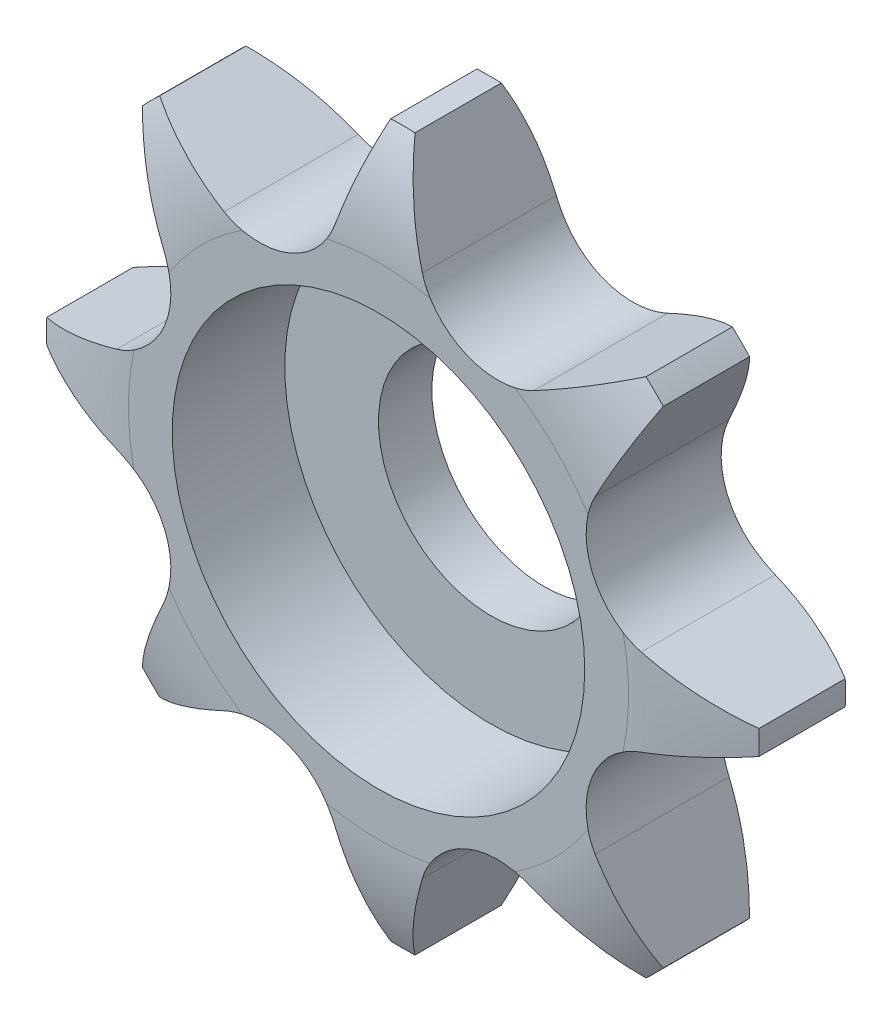
SolidWorks part; units mm, degrees
ref_plane "前视基准面" through (0, 0, 0) normal (0, 0, 1) x (1, 0, 0)
ref_plane "上视基准面" through (0, 0, 0) normal (0, 1, 0) x (1, 0, 0)
ref_plane "右视基准面" through (0, 0, 0) normal (1, 0, 0) x (0, 0, -1)
sketch "草图1" plane through (0, 0, 0) normal (1, 0, 0) x (0, 0, -1)
  line L0 (0, 0) -> (-25, 0) construction
  line L1 (0, 0) -> (0, 10)
  line L2 (0, 10) -> (-17.8, 10)
  line L3 (-25, 5) -> (0, 5)
  line L4 (-19.1, 19) -> (-25, 19)
  line L5 (-25, 19) -> (-25, 0)
  line L6 (-25, 16.59) -> (-17.8, 16.59) construction
  line L8 (-21.4, 16.59) -> (-21.4, 19) construction
  line L9 (-17.8, 16.59) -> (-17.8, 10)
  line L10 (-18, 10) -> (-18, 16.59)
  arc A0 (-17.8, 13.3334) -> (-19.1, 19) centre (-30.8, 13.3334) ccw
  arc A1 (-18, 13.3334) -> (-19.3, 19) centre (-31, 13.3334) ccw
  point P14 (-25, 4)
  point P15 (-18, 10)
  point P17 (-4, 10)
  point P18 (9.9, 10)
  dimension "D1" = 10
  dimension "r" = 13
  dimension "D3" = 13
  dimension "B1" = 7.2
  dimension "D2" = 1.3
  dimension "A" = 25
  dimension "de" = 38
  dimension "Dp" = 33.18
  dimension "Dm" = 20
  dimension "C" = 1.3
  dimension "Z" = 8
  dimension "(b1)" = 7
  dimension "B2" = 21
  dimension "B3" = 34.9
sketch "草图3" plane through (0, 0, 0) normal (0, 0, 1) x (1, 0, 0)
  line L0 (0, 0) -> (0, 19) construction
  line L1 (0, 0) -> (6.35, 15.3266) construction
  line L2 (0.65, 18.9889) -> (2.3119, 13.9854)
  line L3 (0, 13.3518) -> (9.4427, 9.4395) construction
  line L4 (8.2563, 11.5225) -> (12.9699, 13.8846)
  line L5 (-0.65, 18.9889) -> (-2.3119, 13.9854) construction
  line L6 (0, 19) -> (0, 0) construction
  circle A0 centre (0, 0) radius 19 construction
  circle A1 centre (6.35, 15.3266) radius 4.255
  circle A2 centre (-6.35, 15.3266) radius 4.255 construction
  circle A3 centre (0, 0) radius 20.845 construction
  point P13 (-12.9699, 13.8846)
  point P15 (4.7214, 11.3957)
  dimension "D1" = 8.51
  dimension "D3" = 41.69
  dimension "D4" = 1.3
  dimension "D2" = 12.7
sketch "草图4" plane through (0, 0, 0) normal (1, 0, 0) x (0, 0, -1)
  line L1 (-21.4, 16.59) -> (-21.4, 19) construction
  line L2 (-21.4, 16.59) -> (-21.4, 19) construction
  line L3 (0, 10) -> (-17.8, 10)
  line L4 (0, 0) -> (0, 10) construction
  line L6 (0, 5) -> (0, 10)
  line L8 (-25, 19) -> (-25, 0) construction
  line L9 (-19.1, 19) -> (-25, 19) construction
  line L10 (-17.8, 16.59) -> (-17.8, 10) construction
  line L11 (-25, 5) -> (0, 5) construction
  line L12 (-25, 5) -> (0, 5)
  line L14 (-25, 13.3334) -> (-25, 5)
  line L15 (-19.1, 19) -> (-23.7, 19)
  line L16 (-17.8, 13.3334) -> (-17.8, 10)
  arc A0 (-25, 13.3334) -> (-23.7, 19) centre (-12, 13.3334) cw
  arc A1 (-17.8, 13.3334) -> (-19.1, 19) centre (-30.8, 13.3334) ccw construction
  arc A2 (-17.8, 13.3334) -> (-19.1, 19) centre (-30.8, 13.3334) ccw
revolve "旋转1" add sketch "草图4" angle 360 about L0
sketch "草图5" plane through (0, 0, 0) normal (0, 0, 1) x (1, 0, 0)
  line L0 (0.65, 18.9889) -> (2.3119, 13.9854) construction
  line L1 (8.2563, 11.5225) -> (12.9699, 13.8846) construction
  line L2 (0.65, 18.9889) -> (2.3119, 13.9854)
  line L3 (8.2563, 11.5225) -> (12.9699, 13.8846)
  circle A0 centre (6.35, 15.3266) radius 4.255 construction
  arc A1 (2.3119, 13.9854) -> (8.2563, 11.5225) centre (6.35, 15.3266) ccw
  circle A2 centre (0, 0) radius 19 construction
  arc A3 (12.9699, 13.8846) -> (0.65, 18.9889) centre (0, 0) ccw
extrude "切除-拉伸1" cut sketch "草图5" along normal through all
pattern_circular "阵列(圆周)1" count 8 over 360 about axis through (0, 0, 0) along (0, 0, 1) of "切除-拉伸1"
sketch "草图9" [suppressed] plane through (0, 0, 0) normal (1, 0, 0) x (0, 0, -1)
  line L1 (-34.1, 45.05) -> (-40, 45.05) construction
  line L5 (-40, 45.05) -> (-40, 0) construction
  line L6 (-33, 35) -> (-33, 42.61) construction
  line L7 (-34.3, 45.05) -> (-38.7, 45.05)
  line L8 (-40, 39.3834) -> (-40, 35)
  line L10 (-33, 35) -> (-33, 39.3834)
  line L11 (-33, 39.3834) -> (-40, 39.3834) construction
  line L12 (-36.5, 39.3834) -> (-36.5, 45.05) construction
  line L14 (-33, 35) -> (-40, 35)
  arc A0 (-33, 39.3834) -> (-34.3, 45.05) centre (-46, 39.3834) ccw construction
  arc A1 (-33, 39.3834) -> (-34.3, 45.05) centre (-46, 39.3834) ccw
  arc A2 (-40, 39.3834) -> (-38.7, 45.05) centre (-27, 39.3834) cw
revolve "旋转3" [suppressed] add sketch "草图9" angle 360 about L0
sketch "草图10" [suppressed] plane through (0, 0, 0) normal (1, 0, 0) x (0, 0, -1)
  line L0 (0, 35) -> (-32.8, 35) construction
  line L1 (0, 35) -> (-40, 35)
  line L2 (0, 0) -> (0, 35) construction
  line L3 (-40, 8) -> (0, 8) construction
  line L4 (0, 8) -> (0, 35)
  line L5 (-40, 8) -> (0, 8)
  line L6 (-33, 35) -> (-33, 8) construction
  line L7 (-40, 45.05) -> (-40, 0) construction
  line L11 (-40, 35) -> (-40, 8)
revolve "旋转4" [suppressed] add sketch "草图10" angle 360 about L0
sketch "草图8" [suppressed] plane through (0, 0, 0) normal (0, 0, 1) x (1, 0, 0)
  line L0 (0.65, 45.0453) -> (2.3851, 40.5901) construction
  line L1 (9.6837, 39.4901) -> (12.6548, 43.2361) construction
  line L2 (0.65, 45.0453) -> (2.3851, 40.5901)
  line L3 (9.6837, 39.4901) -> (12.6548, 43.2361)
  circle A0 centre (6.35, 42.1342) radius 4.255 construction
  arc A1 (2.3851, 40.5901) -> (9.6837, 39.4901) centre (6.35, 42.1342) ccw
  circle A2 centre (0, 0) radius 45.05 construction
  arc A3 (12.6548, 43.2361) -> (0.65, 45.0453) centre (0, 0) ccw
extrude "切除-拉伸3" [suppressed] cut sketch "草图8" along normal through all
pattern_circular "阵列(圆周)3" [suppressed] count 8 over 360
pattern_linear "阵列(线性)7" [suppressed] count 2 spacing 14 along (0, 0, 1)
sketch "草图11" [suppressed] plane through (0, 0, 0) normal (1, 0, 0) x (0, 0, -1)
  line L0 (-50, 24.95) -> (-50, 0) construction
  line L1 (-50, 24.95) -> (-50, 8) construction
  line L2 (-44.1, 24.95) -> (-50, 24.95) construction
  line L3 (0, 16) -> (-42.8, 16) construction
  line L4 (-43, 19.2675) -> (-50, 19.2675) construction
  line L5 (0, 0) -> (0, 16) construction
  line L7 (-44.1, 24.95) -> (-50, 24.95) construction
  line L8 (-46.5, 19.2675) -> (-46.5, 24.95) construction
  line L9 (-50, 8) -> (0, 8) construction
  line L10 (0, 8) -> (0, 16) construction
  line L11 (-50, 8) -> (0, 8)
  line L16 (-43, 16) -> (-43, 19.2834) construction
  line L17 (0, 16) -> (0, 8)
  line L18 (-43, 16) -> (-43, 22.535) construction
  line L23 (-50, 16) -> (-50, 8)
  line L25 (0, 16) -> (-50, 16)
  arc A3 (-43, 19.2834) -> (-44.3, 24.95) centre (-56, 19.2834) ccw construction
  arc A5 (-43, 19.2834) -> (-44.3, 24.95) centre (-56, 19.2834) ccw construction
revolve "旋转5" [suppressed] add sketch "草图11" angle 360 about L0
sketch "草图12" [suppressed] plane through (0, 0, 0) normal (1, 0, 0) x (0, 0, -1)
  line L0 (-43, 16) -> (-43, 22.535) construction
  line L1 (-43, 19.2834) -> (-50, 19.2834) construction
  line L2 (-44.1, 24.95) -> (-50, 24.95) construction
  line L3 (-50, 24.95) -> (-50, 0) construction
  line L5 (-43, 16) -> (-43, 19.2834)
  line L6 (-46.5, 19.2834) -> (-46.5, 24.95) construction
  line L7 (-43, 16) -> (-50, 16)
  line L8 (-44.3, 24.95) -> (-48.7, 24.95)
  line L9 (-50, 19.2834) -> (-50, 16)
  arc A0 (-43, 19.2834) -> (-44.3, 24.95) centre (-56, 19.2834) ccw construction
  arc A1 (-50, 19.2834) -> (-48.7, 24.95) centre (-37, 19.2834) cw
  arc A3 (-43, 19.2834) -> (-44.3, 24.95) centre (-56, 19.2834) ccw
revolve "旋转6" [suppressed] add sketch "草图12" angle 360 about L0
sketch "草图13" [suppressed] plane through (0, 0, 0) normal (0, 0, 1) x (1, 0, 0)
  line L0 (0.65, 24.9415) -> (2.3419, 20.1936) construction
  line L1 (0.65, 24.9415) -> (2.3419, 20.1936)
  line L2 (8.9493, 18.2531) -> (12.9399, 21.3322) construction
  line L3 (8.9493, 18.2531) -> (12.9399, 21.3322)
  circle A0 centre (6.35, 21.6218) radius 4.255 construction
  arc A1 (2.3419, 20.1936) -> (8.9493, 18.2531) centre (6.35, 21.6218) ccw
  circle A2 centre (0, 0) radius 24.95 construction
  arc A3 (12.9399, 21.3322) -> (0.65, 24.9415) centre (0, 0) ccw
extrude "切除-拉伸4" [suppressed] cut sketch "草图13" along normal through all
pattern_circular "阵列(圆周)4" [suppressed] count 8 over 360
pattern_linear "阵列(线性)9" [suppressed] count 3 spacing 13.95 along (0, 0, 1)
sketch "草图14" plane through (0, 0, 25) normal (0, 0, 1) x (1, 0, 0)
  circle A0 centre (0, 0) radius 6
extrude "切除-拉伸5" cut sketch "草图14" against normal blind 28
sketch "草图15" plane through (0, 0, 25) normal (0, 0, 1) x (1, 0, 0)
  circle A0 centre (0, 0) radius 11
extrude "切除-拉伸6" cut sketch "草图15" against normal blind 6
sketch "草图16" plane through (0, 0, 0) normal (0, 1, 0) x (1, 0, 0)
  line L0 (-15.2872, -16.0399) -> (19.6729, -16.4784)
  dimension "D1" = 34.9629
extrude "切除-拉伸7" cut sketch "草图16" against normal through all and the other way through all
